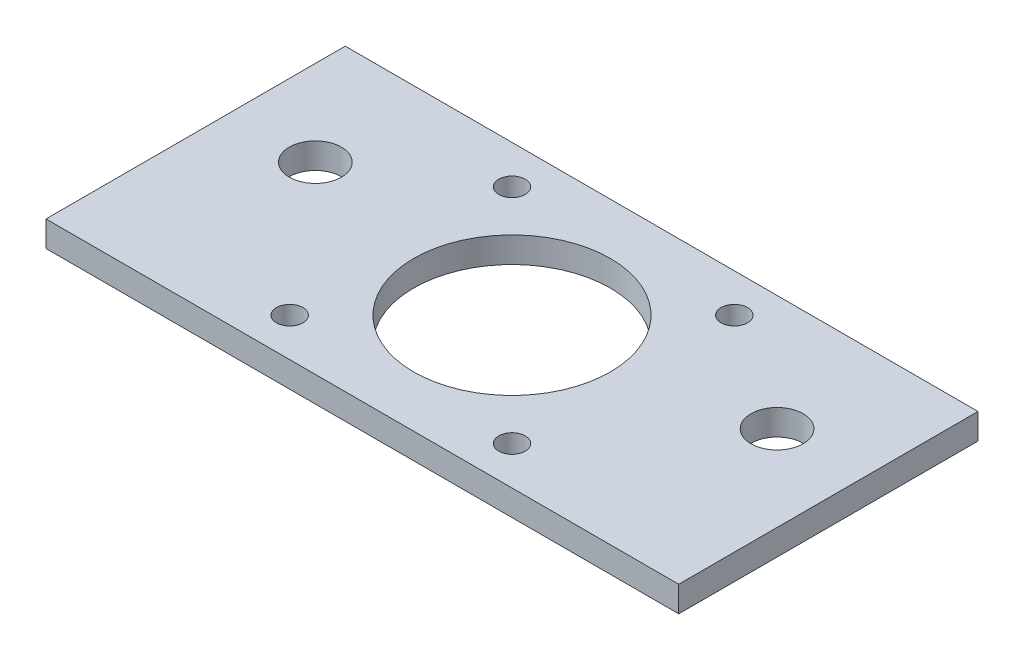
SolidWorks part; units mm, degrees
material "Thornel Mat VMA"
ref_plane "前视基准面" through (0, 0, 0) normal (0, 0, 1) x (1, 0, 0)
ref_plane "上视基准面" through (0, 0, 0) normal (0, 1, 0) x (1, 0, 0)
ref_plane "右视基准面" through (0, 0, 0) normal (1, 0, 0) x (0, 0, -1)
sketch "草图1" plane through (0, 0, 0) normal (0, 1, 0) x (1, 0, 0)
  line L1 (-37, 17.5) -> (37, 17.5)
  line L2 (-37, 17.5) -> (-37, -17.5)
  line L3 (-37, -17.5) -> (37, -17.5)
  line L4 (37, 17.5) -> (37, -17.5)
  line L5 (-37, 17.5) -> (37, -17.5) construction
  line L6 (-37, -17.5) -> (37, 17.5) construction
  point P0 (0, 0)
  dimension "D1" = 74
  dimension "D2" = 35
extrude "凸台-拉伸1" add sketch "草图1" along normal blind 3
ref_plane "基准面1" through (0, 3, 0) normal (0, 1, 0) x (1, 0, 0)
ref_plane "基准面2" through (0, 0, 0) normal (0, -1, 0) x (-1, 0, 0)
sketch "草图3" plane through (0, 0, 0) normal (0, -1, 0) x (-1, 0, 0)
  circle A0 centre (13, -13) radius 1.55
  circle A1 centre (-13, -13) radius 1.55
  circle A2 centre (-13, 13) radius 1.55
  circle A3 centre (13, 13) radius 1.55
  dimension "D1" = 3.1
  dimension "D2" = 3.1
  dimension "D3" = 3.1
  dimension "D4" = 3.1
extrude "切除-拉伸1" cut sketch "草图3" against normal blind 10
sketch "草图4" plane through (0, 3, 0) normal (0, 1, 0) x (1, 0, 0)
  circle A0 centre (-27, 4) radius 3.05
  circle A1 centre (27, 4) radius 3.05
  dimension "D1" = 6.1
  dimension "D2" = 6.1
extrude "切除-拉伸2" cut sketch "草图4" against normal blind 10
sketch "草图5" plane through (0, 0, 0) normal (0, -1, 0) x (-1, 0, 0)
  circle A0 centre (0, 0) radius 11.5
  dimension "D1" = 23
extrude "切除-拉伸3" cut sketch "草图5" against normal blind 10
